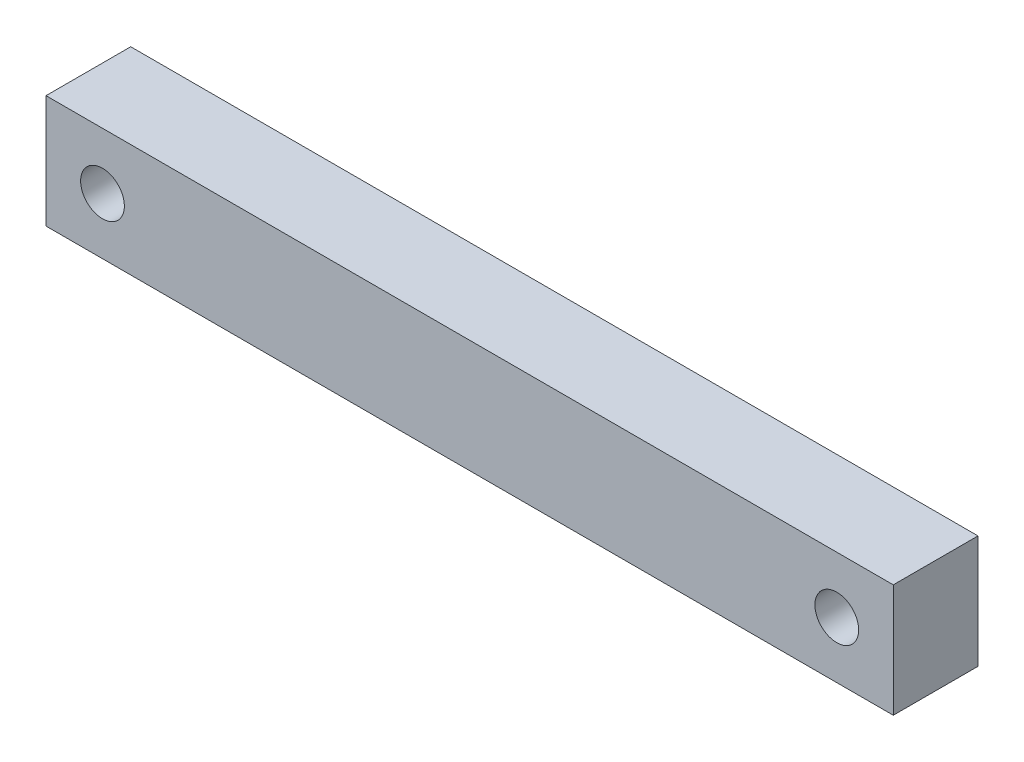
SolidWorks part; units mm, degrees
ref_plane "Płaszczyzna przednia" through (0, 0, 0) normal (0, 0, 1) x (1, 0, 0)
ref_plane "Płaszczyzna górna" through (0, 0, 0) normal (0, 1, 0) x (1, 0, 0)
ref_plane "Płaszczyzna prawa" through (0, 0, 0) normal (1, 0, 0) x (0, 0, -1)
sketch "Szkic1" plane through (0, 0, 0) normal (0, 0, 1) x (1, 0, 0)
  line L0 (29, -171.104) -> (29, -179.104)
  line L1 (29, -171.104) -> (89, -171.104)
  line L2 (29, -179.104) -> (89, -179.104)
  line L3 (89, -171.104) -> (89, -179.104)
  line L7 (25, -195.604) -> (25, -167.604) construction
  line L8 (93, -195.604) -> (93, -167.604) construction
  line L10 (94, -169.604) -> (10.1, -169.604) construction
  circle A0 centre (85, -175.104) radius 1.55
  circle A1 centre (33, -175.104) radius 1.55
  dimension "D3" = 3.1
  dimension "D4" = 3.1
  dimension "D5" = 4
  dimension "D6" = 4
  dimension "D9" = 4
  dimension "D10" = 4
  dimension "D2" = 4
  dimension "D7" = 8
  dimension "D8" = 4
  dimension "D11" = 1.5
extrude "Dodanie-wyciągnięcie1" add sketch "Szkic1" along normal blind 6
